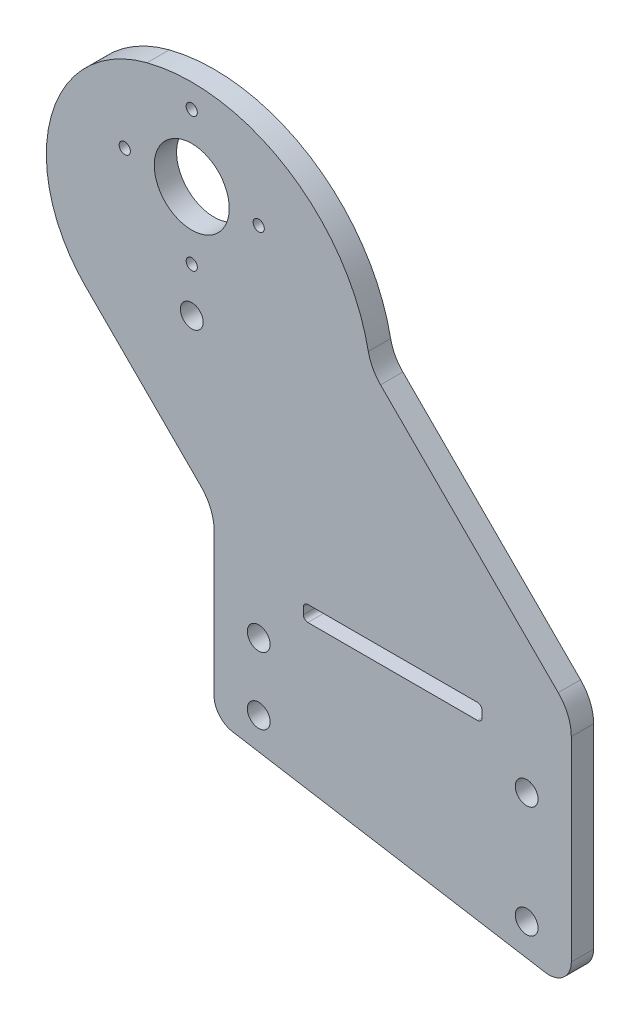
SolidWorks part; units mm, degrees
ref_plane "正面" through (0, 0, 0) normal (0, 0, 1) x (1, 0, 0)
ref_plane "平面" through (0, 0, 0) normal (0, 1, 0) x (1, 0, 0)
ref_plane "右側面" through (0, 0, 0) normal (1, 0, 0) x (0, 0, -1)
sketch "ｽｹｯﾁ1" plane through (0, 0, 0) normal (0, 0, 1) x (1, 0, 0)
  line L0 (-85, -71.4) -> (-85, -11.4) construction
  line L1 (-85, -11.4) -> (-40, 33.6) construction
  line L2 (-40, 33.6) -> (40, 33.6) construction
  line L3 (40, 33.6) -> (85, -11.4)
  line L4 (85, -11.4) -> (85, -71.4)
  line L5 (85, -71.4) -> (-85, -71.4) construction
  line L6 (40, 33.6) -> (-85, -71.4) construction
  line L7 (-40, 33.6) -> (85, -71.4) construction
  line L8 (0, 0) -> (0, -18.9) construction
  line L9 (-75, -61.4) -> (75, -61.4) construction
  line L10 (-75, -61.4) -> (-75, 23.6) construction
  line L11 (-75, 23.6) -> (75, 23.6) construction
  line L12 (75, -61.4) -> (75, 23.6) construction
  line L13 (-75, -61.4) -> (75, 23.6) construction
  line L14 (-75, 23.6) -> (75, -61.4) construction
  line L15 (0, 48.6) -> (0, 0) construction
  line L16 (-40, 33.6) -> (5, -11.4)
  line L17 (5, -11.4) -> (5, -71.4)
  line L18 (5, -71.4) -> (85, -71.4)
  circle A0 centre (75, -31.4) radius 2.55
  circle A1 centre (75, -56.4) radius 2.55
  circle A2 centre (-75, -26.4) radius 2.55 construction
  circle A3 centre (-75, -51.4) radius 2.55 construction
  circle A4 centre (0, 23.6) radius 2.55
  arc A5 (-40, 33.6) -> (40, 33.6) centre (0, 28.6) cw
  circle A6 centre (0, 48.6) radius 8.4
  point P2 (0, 0)
  point P10 (0, -18.9)
  dimension "D9" = 20
  dimension "D13" = 5.1
  dimension "D14" = 5
  dimension "D15" = 16.8
  dimension "D1" = 170
  dimension "D2" = 45
  dimension "D3" = 45
  dimension "D4" = 80
  dimension "D5" = 60
  dimension "D6" = 10
  dimension "D7" = 10
  dimension "D8" = 10
  dimension "D10" = 25
  dimension "D11" = 15
  dimension "D12" = 25
  dimension "D16" = 15
  dimension "D17" = 80
extrude "ﾎﾞｽ - 押し出し1" add sketch "ｽｹｯﾁ1" along normal blind 5
fillet "ﾌｨﾚｯﾄ1" radius 10 3 edges at (85, -11.4, 2.5) (40, 33.6, 2.5) (5, -11.4, 2.5)
sketch "ｽｹｯﾁ2" plane through (0, 0, 5) normal (0, 0, 1) x (1, 0, 0)
  line L0 (15, -71.4) -> (15, -10.4721) construction
  line L1 (5, -71.4) -> (85, -71.4) construction
  line L2 (5, -15.5421) -> (5, -71.4) construction
  line L3 (75, -31.4) -> (15, -31.4) construction
  line L4 (5, -71.4) -> (85, -71.4) construction
  circle A0 centre (15, -46.4) radius 2.55
  circle A1 centre (15, -31.4) radius 2.55
  circle A2 centre (75, -56.4) radius 2.55 construction
  dimension "D2" = 25
  dimension "D1" = 10
extrude "ｶｯﾄ - 押し出し1" cut sketch "ｽｹｯﾁ2" against normal through all
fillet "ﾌｨﾚｯﾄ2" radius 30 1 edges at (-40, 33.6, 2.5)
sketch "ｽｹｯﾁ3" plane through (0, 0, 0) normal (0, 0, -1) x (-1, 0, 0)
  line L0 (-45, -71.4) -> (-45, -21.4) construction
  line L1 (-65, -19.9) -> (-25, -19.9)
  line L2 (-65, -19.9) -> (-65, -22.9)
  line L3 (-65, -22.9) -> (-25, -22.9)
  line L4 (-25, -19.9) -> (-25, -22.9)
  line L5 (-65, -19.9) -> (-25, -22.9) construction
  line L6 (-65, -22.9) -> (-25, -19.9) construction
  line L7 (-5, -71.4) -> (-85, -71.4) construction
  point P0 (-45, -21.4)
  dimension "D1" = 3
  dimension "D2" = 40
  dimension "D3" = 50
extrude "ｶｯﾄ - 押し出し2" cut sketch "ｽｹｯﾁ3" against normal through all
sketch "ｽｹｯﾁ5" plane through (0, 0, 0) normal (0, 0, -1) x (-1, 0, 0)
  line L0 (-25, -22.9) -> (-25, -19.9) construction
  line L1 (-65, -19.9) -> (-25, -19.9)
  line L2 (-65, -19.9) -> (-65, -19.4)
  line L3 (-65, -19.4) -> (-25, -19.4)
  line L4 (-25, -19.9) -> (-25, -19.4)
  dimension "D1" = 0.5
extrude "ｶｯﾄ - 押し出し4" cut sketch "ｽｹｯﾁ5" against normal through all
fillet "ﾌｨﾚｯﾄ3" radius 1 4 edges at (65, -19.4, 2.5) (65, -22.9, 2.5) (25, -22.9, 2.5) (25, -19.4, 2.5)
sketch "ｽｹｯﾁ6" plane through (0, 0, 0) normal (0, 0, -1) x (-1, 0, 0)
  line L0 (-5, -51.8299) -> (-122.4207, -71.4)
  line L1 (-5, -15.5421) -> (-5, -71.4) construction
  line L2 (-5, -71.4) -> (-85, -71.4) construction
  line L3 (-122.4207, -71.4) -> (-5, -71.4)
  line L4 (-5, -71.4) -> (-5, -51.8299)
  line L5 (-15, -46.4) -> (-75, -56.4) construction
  dimension "D1" = 7
extrude "ｶｯﾄ - 押し出し5" cut sketch "ｽｹｯﾁ6" against normal through all
fillet "ﾌｨﾚｯﾄ4" radius 5 2 edges at (85, -65.1632, 2.5) (5, -51.8299, 2.5)
sketch "ｽｹｯﾁ7" plane through (0, 0, 5) normal (0, 0, 1) x (1, 0, 0)
  line L0 (0, 48.6) -> (0, 63.6) construction
  line L1 (-15, 48.6) -> (0, 48.6) construction
  line L2 (0, 48.6) -> (15, 48.6) construction
  circle A0 centre (0, 63.6) radius 1.25
  circle A1 centre (15, 48.6) radius 1.25
  circle A2 centre (0, 33.6) radius 1.25
  circle A3 centre (-15, 48.6) radius 1.25
  dimension "D1" = 2.5
  dimension "D2" = 15
  dimension "D3" = 4
extrude "ｶｯﾄ - 押し出し6" cut sketch "ｽｹｯﾁ7" against normal through all
